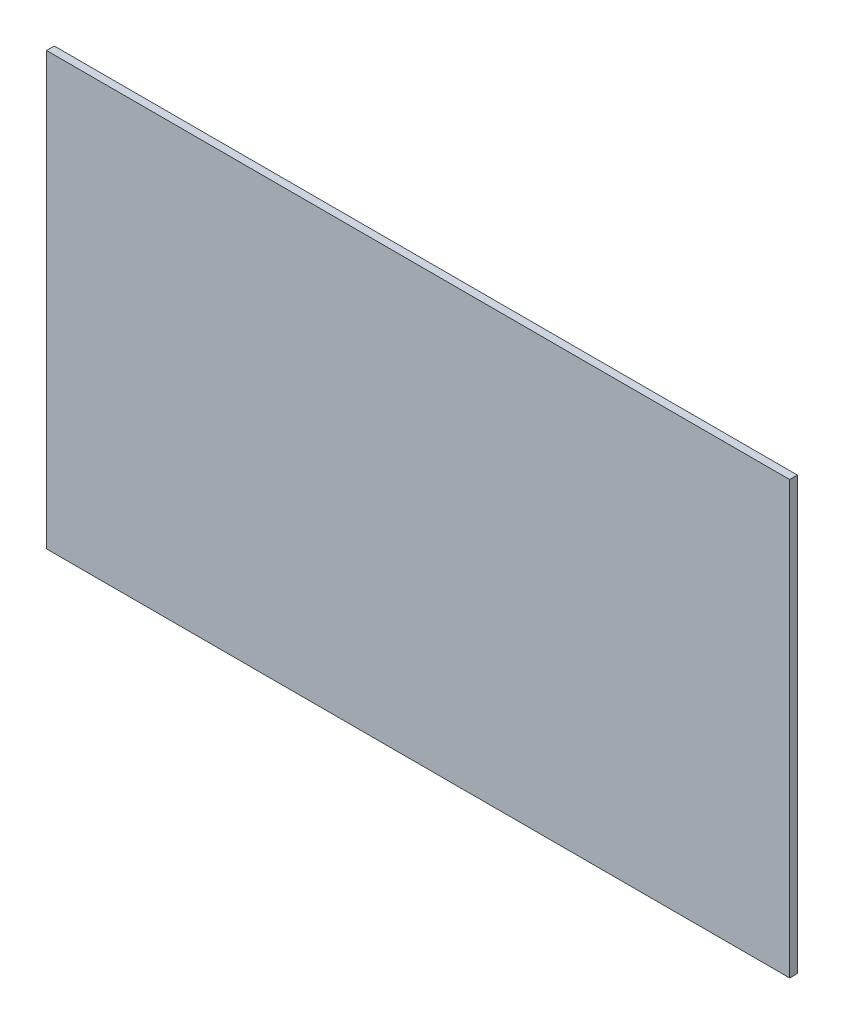
SolidWorks part; units mm, degrees
ref_plane "Front Plane" through (0, 0, 0) normal (0, 0, 1) x (1, 0, 0)
ref_plane "Top Plane" through (0, 0, 0) normal (0, 1, 0) x (1, 0, 0)
ref_plane "Right Plane" through (0, 0, 0) normal (1, 0, 0) x (0, 0, -1)
sketch "Sketch1" plane through (0, 0, 0) normal (0, 0, 1) x (1, 0, 0)
  line L0 (0, -88.519) -> (25.4, -88.519) construction
  line L1 (0, 0) -> (304.8, 0)
  line L2 (0, 0) -> (0, -177.038)
  line L3 (0, -177.038) -> (304.8, -177.038)
  line L4 (304.8, 0) -> (304.8, -177.038)
  dimension "D1" = 304.8
  dimension "D2" = 177.038
extrude "Boss-Extrude1" add sketch "Sketch1" along normal blind 3.175
sketch "Sketch2" plane through (0, -177.038, 0) normal (0, -1, 0) x (1, 0, 0)
  line L0 (304.8, 1.5875) -> (0, 1.5875) construction
  line L1 (304.8, 3.175) -> (304.8, 0) construction
  line L2 (0, 3.175) -> (0, 0) construction
sketch "Sketch4" plane through (0, 0, 0) normal (0, 1, 0) x (1, 0, 0)
  point P3 (0, -1.5875)
sketch "Sketch5" plane through (304.8, 0, 0) normal (1, 0, 0) x (0, 0, -1)
  line L0 (-1.5875, 0) -> (-1.5875, -177.038) construction
  line L1 (-3.175, 0) -> (0, 0) construction
  line L2 (-3.175, -177.038) -> (0, -177.038) construction
sketch "Sketch6" plane through (0, 0, 0) normal (-1, 0, 0) x (0, 0, 1)
  line L0 (1.5875, 0) -> (1.5875, -177.038) construction
  line L1 (3.175, -177.038) -> (0, -177.038) construction
